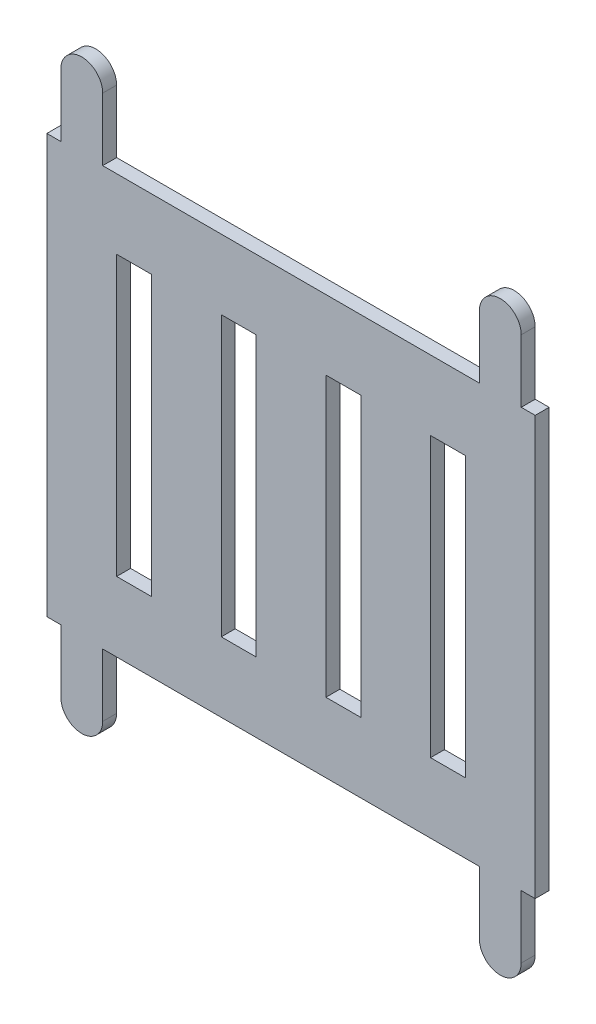
SolidWorks part; units mm, degrees
ref_plane "前视基准面" through (0, 0, 0) normal (0, 0, 1) x (1, 0, 0)
ref_plane "上视基准面" through (0, 0, 0) normal (0, 1, 0) x (1, 0, 0)
ref_plane "右视基准面" through (0, 0, 0) normal (1, 0, 0) x (0, 0, -1)
sketch "草图1" plane through (0, 0, 0) normal (0, 0, 1) x (1, 0, 0)
  line L0 (2, 0) -> (2, -9)
  line L1 (0, 0) -> (2, 0)
  line L2 (0, 0) -> (0, 60)
  line L3 (0, 60) -> (2, 60)
  line L4 (70, 0) -> (70, 60)
  line L6 (8, -9) -> (8, 0)
  line L7 (62, 0) -> (62, -9)
  line L9 (68, -9) -> (68, 0)
  line L10 (2, 60) -> (2, 69)
  line L12 (8, 69) -> (8, 60)
  line L13 (62, 60) -> (62, 69)
  line L15 (68, 69) -> (68, 60)
  line L16 (8, 60) -> (62, 60)
  line L17 (68, 60) -> (70, 60)
  line L18 (68, 0) -> (70, 0)
  line L19 (8, 0) -> (62, 0)
  line L21 (15, 50) -> (10, 50)
  line L22 (15, 50) -> (15, 10)
  line L23 (15, 10) -> (10, 10)
  line L24 (10, 50) -> (10, 10)
  line L25 (30, 50) -> (25, 50)
  line L26 (30, 50) -> (30, 10)
  line L27 (30, 10) -> (25, 10)
  line L28 (25, 50) -> (25, 10)
  line L29 (40, 50) -> (45, 50)
  line L30 (40, 50) -> (40, 10)
  line L31 (40, 10) -> (45, 10)
  line L32 (45, 50) -> (45, 10)
  line L33 (55, 50) -> (60, 50)
  line L34 (55, 50) -> (55, 10)
  line L35 (55, 10) -> (60, 10)
  line L36 (60, 50) -> (60, 10)
  arc A2 (62, -9) -> (68, -9) centre (65, -9) ccw
  arc A3 (2, -9) -> (8, -9) centre (5, -9) ccw
  arc A4 (2, 69) -> (8, 69) centre (5, 69) cw
  arc A5 (62, 69) -> (68, 69) centre (65, 69) cw
extrude "凸台-拉伸1" add sketch "草图1" along normal mid plane 2
